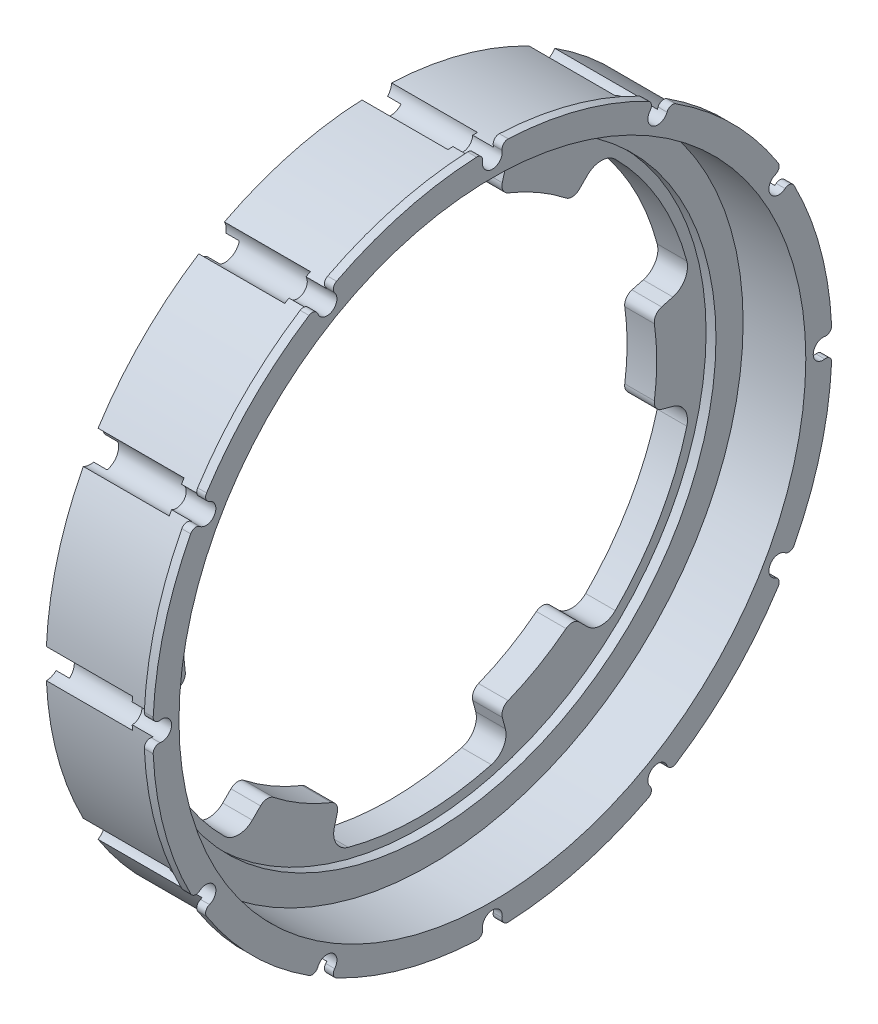
SolidWorks part; units mm, degrees
material "7075-T6 (SN)"
ref_plane "Front Plane" through (0, 0, 0) normal (0, 0, 1) x (1, 0, 0)
ref_plane "Top Plane" through (0, 0, 0) normal (0, 1, 0) x (1, 0, 0)
ref_plane "Right Plane" through (0, 0, 0) normal (1, 0, 0) x (0, 0, -1)
sketch "Sketch1" plane through (0, 0, 0) normal (0, 0, 1) x (1, 0, 0)
  line L0 (0, 0) -> (78.813, 0) construction
  line L1 (0, 0) -> (0, 32.5) construction
  line L2 (0, 24) -> (0, 32.5)
  line L3 (0, 33.5) -> (10.35, 33.5)
  line L4 (10.35, 33.5) -> (10.35, 31.75)
  line L5 (10.35, 31.75) -> (4, 31.75)
  line L6 (4, 31.75) -> (4, 29)
  line L7 (0, 24) -> (3, 24)
  line L8 (3, 24) -> (3, 29)
  line L9 (3, 29) -> (4, 29)
  line L10 (0, 32.5) -> (-1.3625, 32.5)
  line L11 (-1.3625, 32.5) -> (-1.3625, 33.5)
  line L12 (0, 33.5) -> (0, 53.3389) construction
  line L13 (-1.3625, 33.5) -> (0, 33.5)
  dimension "D1" = 6.35
  dimension "D2" = 33.5
  dimension "D3" = 63.5
  dimension "D4" = 11.7125
  dimension "D5" = 58
  dimension "D6" = 3
  dimension "D7" = 5
  dimension "D8" = 1
  dimension "D9" = 1
revolve "Revolve1" add sketch "Sketch1" angle 360 about L0
sketch "Sketch2" plane through (3, 0, 0) normal (1, 0, 0) x (0, 0, -1)
  line L0 (0, 0) -> (0, 36.6466) construction
  line L1 (0, 0) -> (9.0857, 33.9082) construction
  line L2 (8.6611, 24.5964) -> (8.1219, 22.5839)
  line L3 (0, 28) -> (0, 24)
  line L4 (0, 0) -> (0, 38.4869) construction
  arc A0 (8.6611, 24.5964) -> (7.2469, 27.0459) centre (6.7293, 25.1141) ccw
  circle A1 centre (0, 0) radius 24 construction
  arc A2 (7.2469, 27.0459) -> (0, 28) centre (0, 0) ccw
  arc A3 (8.1219, 22.5839) -> (0, 24) centre (0, 0) ccw
  dimension "D2" = 2
  dimension "D3" = 0
  dimension "D1" = 15
extrude "Cut-Extrude1" cut sketch "Sketch2" against normal blind 10
mirror "Mirror1" about plane through (-7, 28, 0) normal (0, 0, 1) of "Cut-Extrude1"
fillet "Fillet1" radius 1 2 edges at (1.5, 22.5839, 8.1219) (1.5, 22.5839, -8.1219)
pattern_circular "CirPattern2" count 6 over 360 about axis through (0, 0, 0) along (1, 0, 0) of "Mirror1", "Cut-Extrude1", "Fillet1"
sketch "Sketch5" plane through (10.35, 0, 0) normal (1, 0, 0) x (0, 0, -1)
  circle A0 centre (0, 0) radius 34.4
  circle A1 centre (0, 0) radius 33.5 construction
  circle A2 centre (0, 0) radius 33.5
  dimension "D1" = 0.9
extrude "Boss-Extrude1" add sketch "Sketch5" against normal blind 0.9
sketch "Sketch3" plane through (10.35, 0, 0) normal (1, 0, 0) x (0, 0, -1)
  circle A0 centre (0, 33.5) radius 1.5
  circle A1 centre (0, 0) radius 33.5 construction
  dimension "D1" = 3
extrude "Cut-Extrude2" cut sketch "Sketch3" against normal through all from offset 3 offset against normal yes
sketch "Sketch4" plane through (7.35, 0, 0) normal (-1, 0, 0) x (0, 0, 1)
  circle A0 centre (0, 33.5) radius 1
  arc A1 (1.4996, 33.4664) -> (-1.4996, 33.4664) centre (0, 0) ccw construction
  dimension "D1" = 2
extrude "Cut-Extrude3" cut sketch "Sketch4" against normal blind 10
fillet "Fillet2" radius 0.6 2 edges at (9.9, 34.3972, 0.4417) (9.9, 34.3972, -0.4417)
pattern_circular "CirPattern3" count 12 over 360 about axis through (0, 0, 0) along (1, 0, 0) of "Cut-Extrude2", "Cut-Extrude3", "Fillet2"
